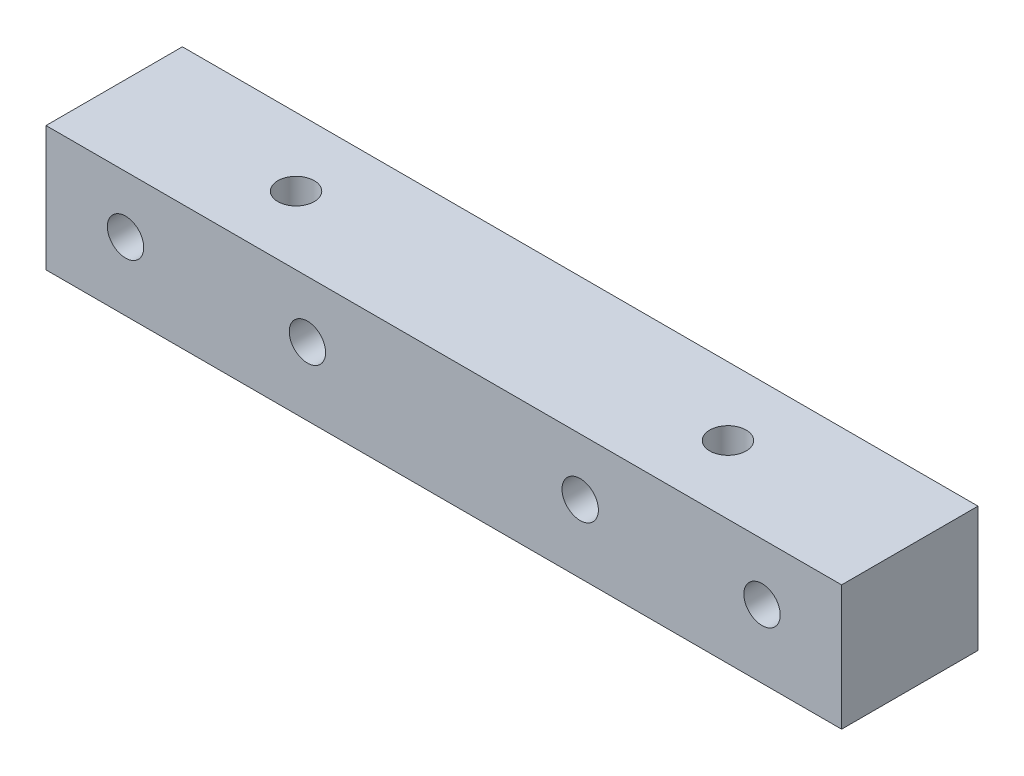
SolidWorks part; units mm, degrees
ref_plane "Front Plane" through (0, 0, 0) normal (0, 0, 1) x (1, 0, 0)
ref_plane "Top Plane" through (0, 0, 0) normal (0, 1, 0) x (1, 0, 0)
ref_plane "Right Plane" through (0, 0, 0) normal (1, 0, 0) x (0, 0, -1)
sketch "Sketch1" plane through (0, 0, 0) normal (0, 1, 0) x (1, 0, 0)
  line L1 (-17.5, 3) -> (17.5, 3)
  line L2 (-17.5, 3) -> (-17.5, -3)
  line L3 (-17.5, -3) -> (17.5, -3)
  line L4 (17.5, 3) -> (17.5, -3)
  line L5 (-17.5, 3) -> (17.5, -3) construction
  line L6 (-17.5, -3) -> (17.5, 3) construction
  point P0 (0, 0)
  dimension "D1" = 35
  dimension "D2" = 6
extrude "Boss-Extrude1" add sketch "Sketch1" along normal blind 5.5
hole_wizard "M2x0.4 Tapped Hole1" positions "Sketch3" profile "Sketch2" tap size "M2x0.4" standard "Ansi Metric" end condition up to next
sketch "Sketch3" plane through (0, 0, 3) normal (0, 0, 1) x (1, 0, 0)
  line L1 (0, 0) -> (0, 5.5) construction
  line L3 (-17.5, 5.5) -> (17.5, 5.5) construction
  line L4 (-17.5, 0) -> (17.5, 0) construction
  point P0 (6, 3)
  point P1 (-14, 3)
  point P3 (-6, 3)
  point P5 (14, 3)
  dimension "D1" = 3
  dimension "D2" = 6
  dimension "D3" = 8
  dimension "D4" = 6
  dimension "D5" = 8
sketch "Sketch2" plane through (6, 3, 3) normal (1, 0, 0) x (0, -1, 0)
  line L0 (0, 0) -> (0, 6)
  line L1 (0, 6) -> (0.8, 6)
  line L2 (0.8, 6) -> (0.8, 0)
  line L5 (0.8, 0) -> (0, 0)
  line L11 (0, -6.35) -> (0, 107.95) construction
  dimension "Thru Tap Drill Dia." = 1.6
  dimension "Thru Tap Drill Depth" = 6
cosmetic thread "Hole Thread7"
cosmetic thread "Hole Thread8"
cosmetic thread "Hole Thread9"
cosmetic thread "Hole Thread10"
hole_wizard "M2x0.4 Tapped Hole2" positions "Sketch5" profile "Sketch4" tap size "M2x0.4" standard "Ansi Metric" end condition up to next
sketch "Sketch5" plane through (0, 5.5, 0) normal (0, 1, 0) x (-1, 0, 0)
  line L1 (17.5, 3) -> (-17.5, 3) construction
  line L2 (17.5, -3) -> (17.5, 3) construction
  line L3 (-17.5, 3) -> (-17.5, -3) construction
  point P0 (9.5, 0)
  point P1 (-9.5, 0)
  dimension "D1" = 3
  dimension "D2" = 8
  dimension "D3" = 8
sketch "Sketch4" plane through (-9.5, 5.5, 0) normal (1, 0, 0) x (0, 0, 1)
  line L0 (0, 0) -> (0, 5.5)
  line L1 (0, 5.5) -> (0.8, 5.5)
  line L2 (0.8, 5.5) -> (0.8, 0)
  line L5 (0.8, 0) -> (0, 0)
  line L11 (0, -6.35) -> (0, 107.95) construction
  dimension "Thru Tap Drill Dia." = 1.6
  dimension "Thru Tap Drill Depth" = 5.5
cosmetic thread "Hole Thread5"
cosmetic thread "Hole Thread6"
